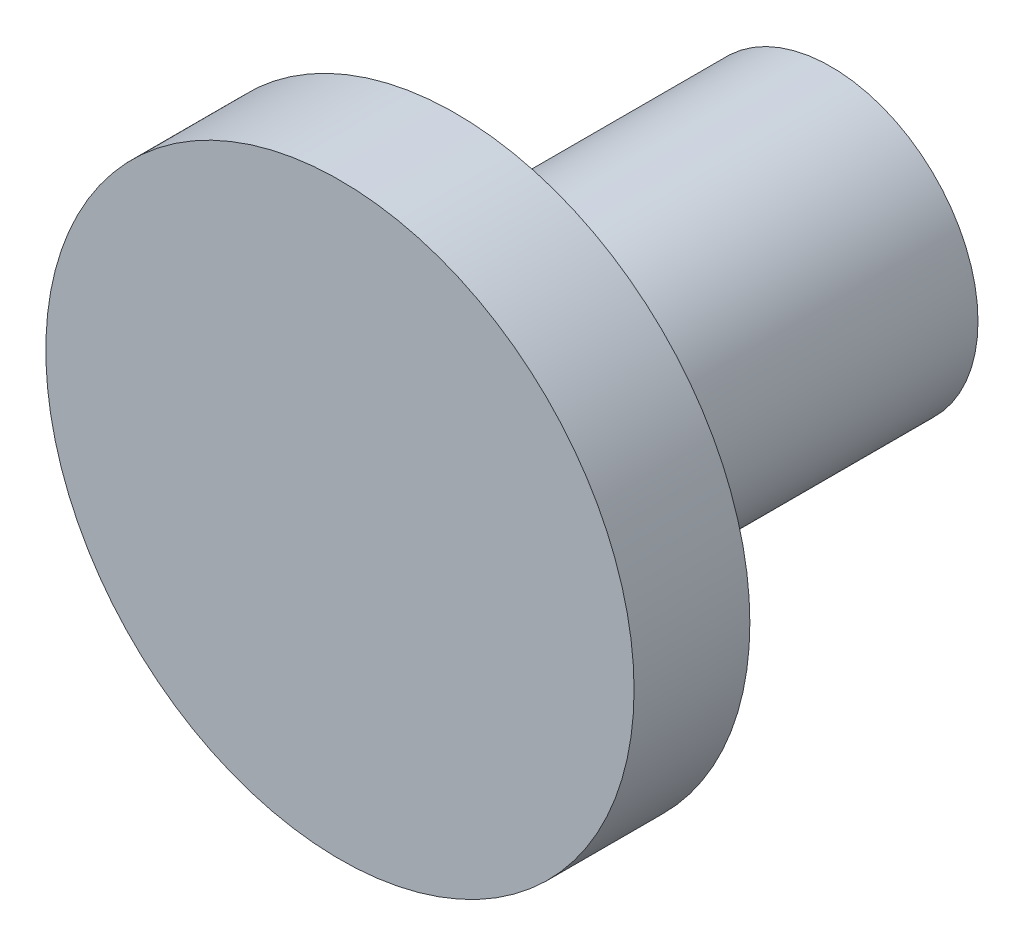
SolidWorks part; units mm, degrees
ref_plane "Alzado" through (0, 0, 0) normal (0, 0, 1) x (1, 0, 0)
ref_plane "Planta" through (0, 0, 0) normal (0, 1, 0) x (1, 0, 0)
ref_plane "Vista lateral" through (0, 0, 0) normal (1, 0, 0) x (0, 0, -1)
sketch "Croquis1" plane through (0, 0, 0) normal (0, 0, 1) x (1, 0, 0)
  circle A0 centre (0, 0) radius 12.7
  dimension "D1" = 25.4
extrude "Saliente-Extruir1" add sketch "Croquis1" along normal blind 5
sketch "Croquis2" plane through (0, 0, 0) normal (0, 0, -1) x (-1, 0, 0)
  circle A0 centre (0, 0) radius 6.35
  dimension "D1" = 12.7
extrude "Saliente-Extruir2" add sketch "Croquis2" along normal blind 16.2
